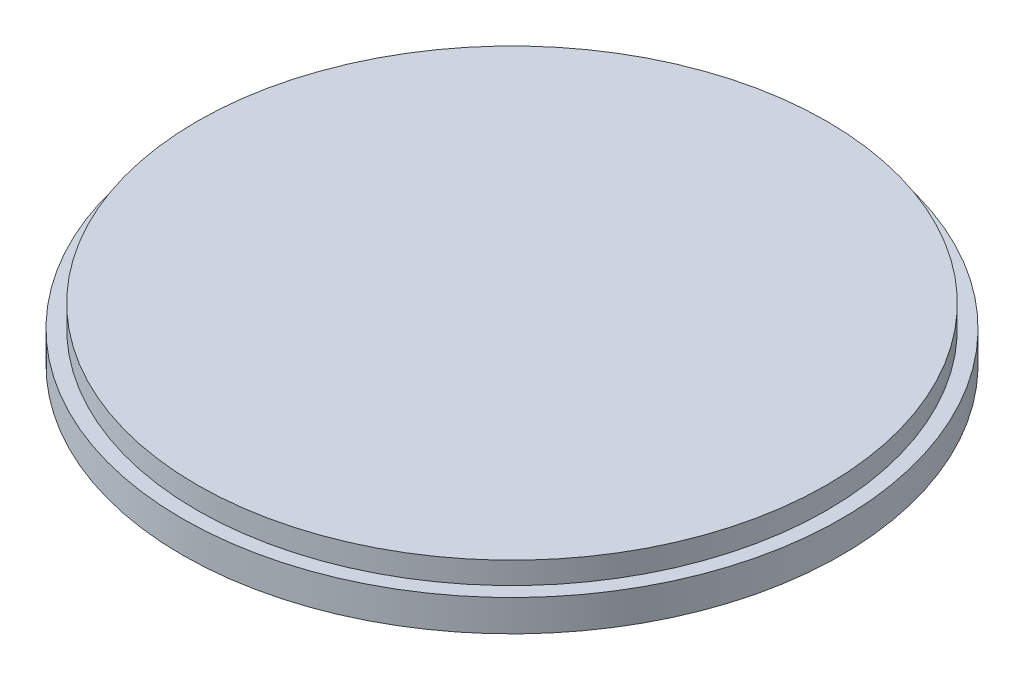
SolidWorks part; units mm, degrees
ref_plane "Front Plane" through (0, 0, 0) normal (0, 0, 1) x (1, 0, 0)
ref_plane "Top Plane" through (0, 0, 0) normal (0, 1, 0) x (1, 0, 0)
ref_plane "Right Plane" through (0, 0, 0) normal (1, 0, 0) x (0, 0, -1)
sketch "Sketch1" plane through (0, 0, 0) normal (0, 0, 1) x (1, 0, 0)
  line L0 (0, -12.6) -> (0, -7) construction
  line L1 (0, -12.6) -> (-26.5, -12.6) construction
  line L2 (-26.5, -12.6) -> (-26.5, -7) construction
  line L3 (-26.5, -7) -> (-45, -4.3)
  line L4 (-45, -4.3) -> (-45, 0)
  line L5 (-45, 0) -> (0, 0)
  line L6 (-26.5, -7) -> (0, -7)
  line L7 (0, -7) -> (0, 0)
  point P4 (0, 0)
  dimension "D1" = 26.5
  dimension "D2" = 5.6
  dimension "D3" = 2.7
  dimension "D4" = 4.3
  dimension "D5" = 45
revolve "Revolve1" add sketch "Sketch1" angle 360 about L7
sketch "Sketch2" plane through (0, 0, 0) normal (0, 1, 0) x (1, 0, 0)
  circle A2 centre (0, 0) radius 43
  circle A3 centre (0, 0) radius 43
  dimension "D1" = 2
extrude "Boss-Extrude1" add sketch "Sketch2" along normal blind 3
sketch "Sketch3" plane through (0, -7, 0) normal (0, -1, 0) x (1, 0, 0)
  line L0 (-15.5563, -15.5563) -> (15.5563, 15.5563) construction
  line L1 (15.5563, -15.5563) -> (-15.5563, 15.5563) construction
  line L2 (0, 0) -> (0, 22) construction
  circle A0 centre (0, 0) radius 22 construction
  point P6 (0, 0)
  point P8 (0, 0)
  dimension "D1" = 44
  dimension "D2" = 45
hole_wizard "M3 Clearance Hole1" positions "Sketch4" profile "Sketch5" hole size "M3" standard "ANSI Metric"
sketch "Sketch4" plane through (0, -7, 0) normal (0, -1, 0) x (-1, 0, 0)
  point P0 (15.5563, -15.5563)
  point P3 (15.5563, 15.5563)
  point P6 (-15.5563, 15.5563)
  point P9 (-15.5563, -15.5563)
sketch "Sketch5" plane through (-15.5563, -7, 15.5563) normal (1, 0, 0) x (0, 0, -1)
  line L0 (0, 0) -> (0, 5.0215)
  line L1 (0, 5.0215) -> (1.7, 4)
  line L2 (1.7, 4) -> (1.7, 0)
  line L5 (1.7, 0) -> (0, 0)
  line L10 (0, 5.0215) -> (-1.7, 4) construction
  line L11 (0, -6.35) -> (0, 107.95) construction
  dimension "Hole Dia." = 3.4
  dimension "Hole Depth" = 4
  dimension "Drill Angle" = 118
